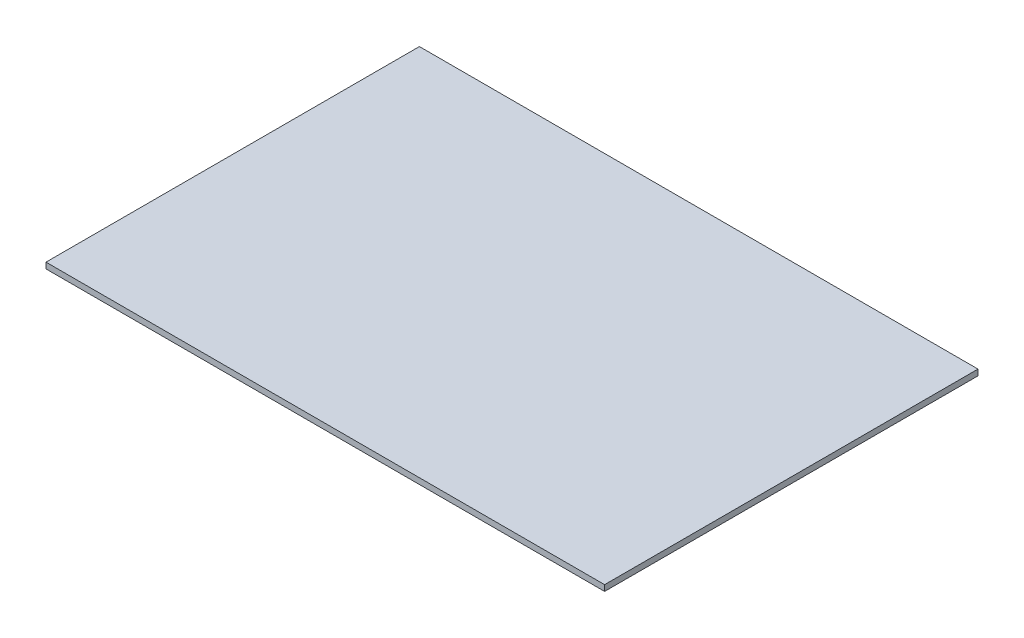
SolidWorks part; units mm, degrees
ref_plane "前基準面" through (0, 0, 0) normal (0, 0, 1) x (1, 0, 0)
ref_plane "上基準面" through (0, 0, 0) normal (0, 1, 0) x (1, 0, 0)
ref_plane "右基準面" through (0, 0, 0) normal (1, 0, 0) x (0, 0, -1)
sketch "草圖1" plane through (0, 0, 0) normal (0, 1, 0) x (1, 0, 0)
  line L1 (225, -150.4) -> (-225, -150.4)
  line L2 (225, -150.4) -> (225, 150.4)
  line L3 (225, 150.4) -> (-225, 150.4)
  line L4 (-225, -150.4) -> (-225, 150.4)
  line L5 (225, -150.4) -> (-225, 150.4) construction
  line L6 (225, 150.4) -> (-225, -150.4) construction
  point P0 (0, 0)
  dimension "D1" = 450
  dimension "D2" = 300.8
extrude "填料-伸長1" add sketch "草圖1" along normal blind 4.75
